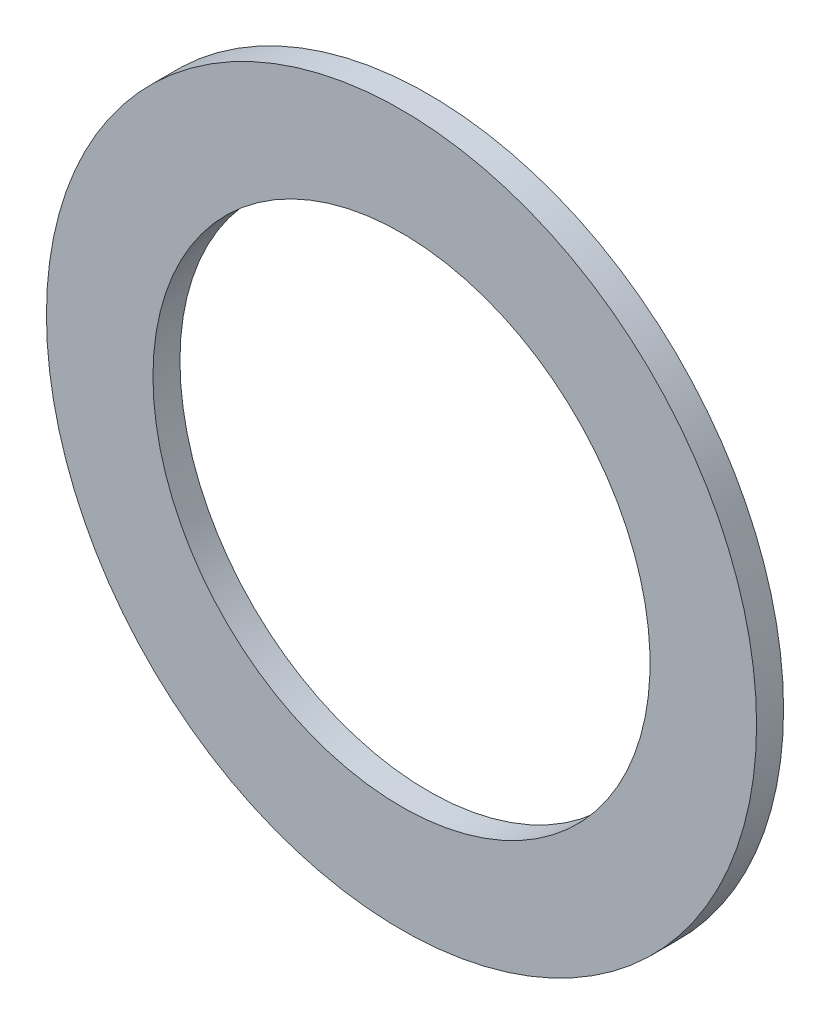
SolidWorks part; units mm, degrees
material "AISI 1020"
ref_plane "Plano frontal" through (0, 0, 0) normal (0, 0, 1) x (1, 0, 0)
ref_plane "Plano superior" through (0, 0, 0) normal (0, 1, 0) x (1, 0, 0)
ref_plane "Plano direito" through (0, 0, 0) normal (1, 0, 0) x (0, 0, -1)
sketch "Esboço1" plane through (0, 0, 0) normal (0, 0, 1) x (1, 0, 0)
  circle A0 centre (0, 0) radius 8.75
  circle A1 centre (0, 0) radius 12.5
  dimension "D1" = 17.5
  dimension "D2" = 25
extrude "Extrusão1" add sketch "Esboço1" along normal blind 0.95
